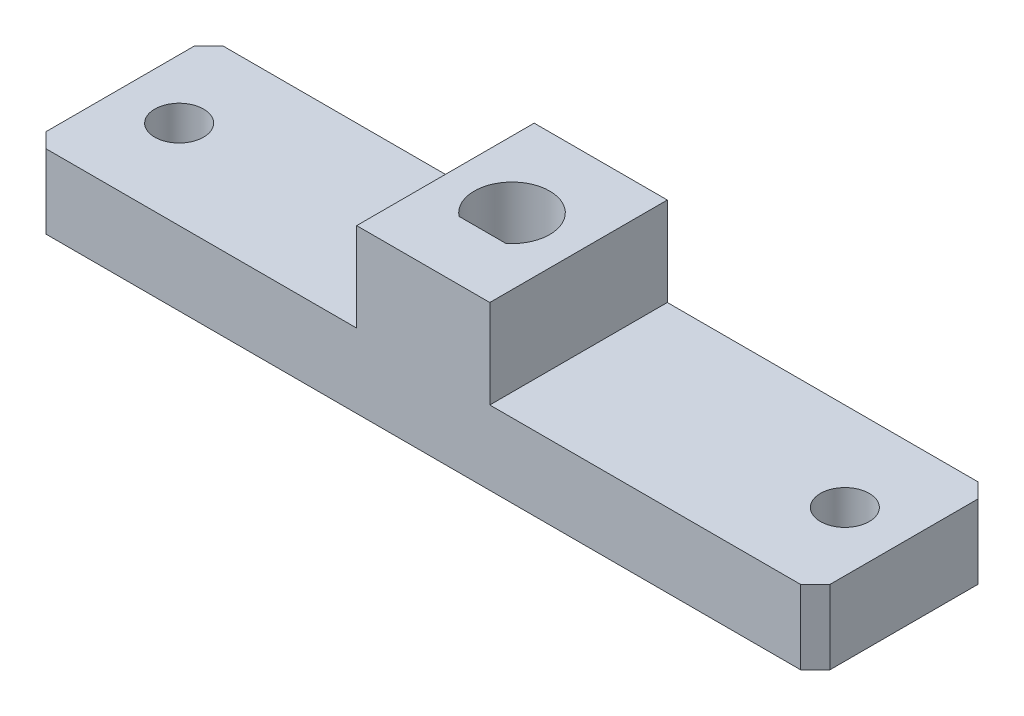
SolidWorks part; units mm, degrees
ref_plane "Top" through (0, 0, 0) normal (0, 0, 1) x (1, 0, 0)
ref_plane "Front" through (0, 0, 0) normal (0, 1, 0) x (1, 0, 0)
ref_plane "Right" through (0, 0, 0) normal (1, 0, 0) x (0, 0, -1)
sketch "Sketch1" plane through (0, 0, 0) normal (0, 0, 1) x (1, 0, 0)
  line L0 (-26.5, 0) -> (26.5, 0)
  line L1 (26.5, 0) -> (26.5, 5)
  line L2 (26.5, 5) -> (4.5, 5)
  line L3 (4.5, 5) -> (4.5, 11)
  line L4 (4.5, 11) -> (-4.5, 11)
  line L5 (-4.5, 11) -> (-4.5, 5)
  line L6 (-4.5, 5) -> (-26.5, 5)
  line L7 (-26.5, 5) -> (-26.5, 0)
  point P8 (0, 0)
  point P9 (26.5, 0)
  dimension "D1" = 53
  dimension "D2" = 9
  dimension "D3" = 5
  dimension "D4" = 6
extrude "Body Extrude" add sketch "Sketch1" against normal blind 12
sketch "Sketch2" plane through (0, 0, 0) normal (0, 1, 0) x (1, 0, 0)
  line L0 (-22.5, 6) -> (22.5, 6) construction
  line L1 (-1.5819, 4) -> (1.5819, 4)
  line L2 (0, 4) -> (0, 8.55) construction
  arc A2 (1.5819, 4) -> (-1.5819, 4) centre (0, 6) ccw
  point P8 (0, 6)
  dimension "D3" = 5.1
  dimension "D1" = 6
  dimension "D2" = 45
  dimension "D4" = 4.55
hole_wizard "M4x0.7 Tapped Hole6" positions "Sketch5" profile "Sketch6" tap size "M4x0.7" standard "ANSI Metric" end condition through all
sketch "Sketch5" plane through (0, 0, 0) normal (0, 1, 0) x (1, 0, 0)
  line L0 (-22.5, 6) -> (22.5, 6) construction
  line L2 (0, 0) -> (0, 6) construction
  point P0 (-22.5, 6)
  point P2 (22.5, 6)
  dimension "D1" = 45
  dimension "D2" = 6
sketch "Sketch6" plane through (-22.5, 0, -6) normal (1, 0, 0) x (0, 0, -1)
  line L0 (0, 0) -> (0, 11)
  line L1 (0, 11) -> (1.65, 11)
  line L2 (1.65, 11) -> (1.65, 0.375)
  line L3 (1.65, 0.375) -> (2.025, 0)
  line L5 (2.025, 0) -> (0, 0)
  line L6 (-1.65, 0.375) -> (-2.025, 0) construction
  line L11 (0, -6.35) -> (0, 107.95) construction
  dimension "Thru Tap Drill Dia." = 3.3
  dimension "Thru Tap Drill Depth" = 11
  dimension "Near C'Sink Dia." = 4.05
  dimension "Near C'Sink Angle" = 90
cosmetic thread "Hole Thread1" parameters "D2"=4
cosmetic thread "Hole Thread2" parameters "D2"=4
extrude "Cut-Extrude1" cut sketch "Sketch2" along normal through all
chamfer "Chamfer1" distance 1 angle 45 4 edges at (-26.5, 2.5, -12) (-26.5, 2.5, 0) (26.5, 2.5, -12) (26.5, 2.5, 0)
equation "\"Height\"= 12mm"
equation "\"D1@Body Extrude\"=\"Height\""
equation "\"D1@Sketch2\"=0.5*\"Height\""
equation "\"D2@Sketch5\"=0.5*\"Height\""
